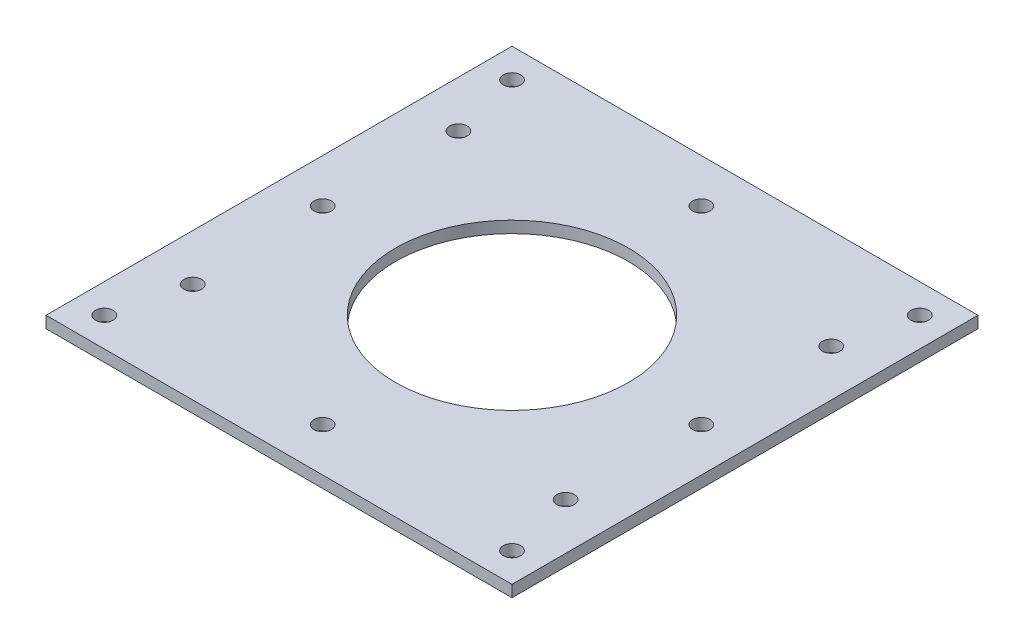
SolidWorks part; units mm, degrees
ref_plane "Front Plane" through (0, 0, 0) normal (0, 0, 1) x (1, 0, 0)
ref_plane "Top Plane" through (0, 0, 0) normal (0, 1, 0) x (1, 0, 0)
ref_plane "Right Plane" through (0, 0, 0) normal (1, 0, 0) x (0, 0, -1)
sketch "Sketch1" plane through (0, 0, 0) normal (0, 1, 0) x (1, 0, 0)
  line L1 (0, 0) -> (80, 0)
  line L2 (0, 0) -> (0, 80)
  line L3 (0, 80) -> (80, 80)
  line L4 (80, 0) -> (80, 80)
  dimension "D1" = 80
  dimension "D2" = 80
extrude "Boss-Extrude1" add sketch "Sketch1" along normal blind 2
sketch "Sketch2" plane through (0, 2, 0) normal (0, 1, 0) x (1, 0, 0)
  line L0 (0, 80) -> (80, 0) construction
  circle A0 centre (40, 40) radius 15
  dimension "D1" = 30
extrude "Cut-Extrude1" [suppressed] cut sketch "Sketch2" against normal through all
sketch "Sketch3" [suppressed] plane through (0, 2, 0) normal (0, 1, 0) x (1, 0, 0)
  arc A0 (1.5119, 76.9578) -> (4.0119, 76.9578) centre (2.7619, 76.9578) ccw construction
  arc A1 (4.0119, 76.9578) -> (1.5119, 76.9578) centre (2.7619, 76.9578) ccw construction
  arc A2 (-6.4881, 86.4578) -> (-3.9881, 86.4578) centre (-5.2381, 86.4578) ccw construction
  arc A3 (-3.9881, 86.4578) -> (-6.4881, 86.4578) centre (-5.2381, 86.4578) ccw construction
  arc A4 (-11.9881, 76.9578) -> (-14.4881, 76.9578) centre (-13.2381, 76.9578) ccw construction
  arc A5 (-14.4881, 76.9578) -> (-11.9881, 76.9578) centre (-13.2381, 76.9578) ccw construction
  arc A6 (-3.9881, 67.4578) -> (-6.4881, 67.4578) centre (-5.2381, 67.4578) ccw construction
  arc A7 (-6.4881, 67.4578) -> (-3.9881, 67.4578) centre (-5.2381, 67.4578) ccw construction
  arc A8 (1.5119, 76.9578) -> (4.0119, 76.9578) centre (2.7619, 76.9578) ccw construction
  arc A9 (4.0119, 76.9578) -> (1.5119, 76.9578) centre (2.7619, 76.9578) ccw construction
  arc A10 (-6.4881, 86.4578) -> (-3.9881, 86.4578) centre (-5.2381, 86.4578) ccw construction
  arc A11 (-3.9881, 86.4578) -> (-6.4881, 86.4578) centre (-5.2381, 86.4578) ccw construction
  arc A12 (-11.9881, 76.9578) -> (-14.4881, 76.9578) centre (-13.2381, 76.9578) ccw construction
  arc A13 (-14.4881, 76.9578) -> (-11.9881, 76.9578) centre (-13.2381, 76.9578) ccw construction
  arc A14 (-3.9881, 67.4578) -> (-6.4881, 67.4578) centre (-5.2381, 67.4578) ccw construction
  arc A15 (-6.4881, 67.4578) -> (-3.9881, 67.4578) centre (-5.2381, 67.4578) ccw construction
  circle A17 centre (-13.2381, 76.9578) radius 1.5
  circle A18 centre (-5.2381, 67.4578) radius 1.5
  circle A19 centre (2.7619, 76.9578) radius 1.5
  circle A20 centre (-5.2381, 86.4578) radius 1.5
  dimension "D1" = 3
extrude "Cut-Extrude2" [suppressed] cut sketch "Sketch3" against normal through all
sketch "Sketch4" plane through (0, 0, 0) normal (0, -1, 0) x (1, 0, 0)
  line L0 (0, 0) -> (80, 0) construction
  line L1 (0, -80) -> (0, 0) construction
  line L2 (40, 0) -> (40, -80) construction
  line L3 (80, -80) -> (0, -80) construction
  line L4 (0, -40) -> (80, -40) construction
  line L5 (80, 0) -> (80, -80) construction
  circle A0 centre (5, -5) radius 1.5
  circle A1 centre (75, -5) radius 1.5
  circle A2 centre (75, -75) radius 1.5
  circle A3 centre (5, -75) radius 1.5
  dimension "D1" = 3
  dimension "D2" = 5
  dimension "D3" = 5
extrude "Cut-Extrude3" cut sketch "Sketch4" against normal through all
sketch "Sketch6" plane through (0, 2, 0) normal (0, 1, 0) x (1, 0, 0)
  circle A0 centre (72, 17.2) radius 2.6 construction
  circle A1 centre (8, 17.2) radius 2.6 construction
  circle A2 centre (72, 17.2) radius 2.6 construction
  circle A3 centre (8, 17.2) radius 2.6 construction
  circle A4 centre (8, 17.2) radius 1.5
  circle A5 centre (72, 17.2) radius 1.5
  dimension "D1" = 3
extrude "Cut-Extrude4" cut sketch "Sketch6" against normal through all
ref_plane "Plane1" through (0, 0, -40) normal (0, 0, 1) x (1, 0, 0)
mirror "Mirror1" about plane through (0, 0, -40) normal (0, 0, 1) of "Cut-Extrude4"
sketch "Sketch7" plane through (0, 2, 0) normal (0, 1, 0) x (1, 0, 0)
  line L1 (30, 9) -> (50, 9)
  line L2 (30, 9) -> (30, 12)
  line L3 (30, 12) -> (50, 12)
  line L4 (50, 9) -> (50, 12)
  line L5 (30, 12) -> (16, 12) construction
  line L6 (16, 19) -> (16, 10.8) construction
  line L7 (50, 12) -> (64, 12) construction
  line L8 (64, 10.8) -> (64, 19) construction
  line L9 (80, 7) -> (0, 7) construction
  line L10 (0, 40) -> (80, 40) construction
  line L11 (0, 80) -> (0, 0) construction
  line L12 (80, 0) -> (80, 80) construction
  line L13 (30, 68) -> (50, 68)
  line L14 (50, 71) -> (50, 68)
  line L15 (30, 71) -> (50, 71)
  line L16 (30, 71) -> (30, 68)
  dimension "D1" = 20
  dimension "D2" = 3
  dimension "D3" = 2
extrude "Cut-Extrude5" [suppressed] cut sketch "Sketch7" against normal through all
sketch "Sketch8" plane through (0, 2, 0) normal (0, 1, 0) x (1, 0, 0)
  line L0 (0, 80) -> (80, 0) construction
  circle A0 centre (40, 40) radius 20
  circle A1 centre (40, 72.5) radius 1.5
  circle A2 centre (72.5, 40) radius 1.5
  circle A3 centre (40, 40) radius 20 construction
  circle A4 centre (40, 7.5) radius 1.5
  circle A5 centre (40, 40) radius 20 construction
  circle A6 centre (7.5, 40) radius 1.5
  circle A7 centre (40, 40) radius 20 construction
  circle A8 centre (40, 40) radius 32.5 construction
  point P9 (0, 0)
  point P10 (40, 72.5)
  dimension "D1" = 40
  dimension "D2" = 3
  dimension "D4" = 65
  dimension "D3" = 4
extrude "Cut-Extrude6" cut sketch "Sketch8" against normal through all
equation "\"D4@Sketch8\"=32.5*2"
